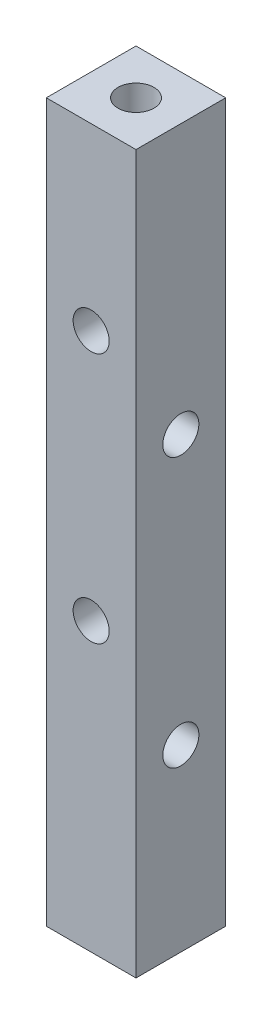
SolidWorks part; units mm, degrees
ref_plane "Front Plane" through (0, 0, 0) normal (0, 0, 1) x (1, 0, 0)
ref_plane "Top Plane" through (0, 0, 0) normal (0, 1, 0) x (1, 0, 0)
ref_plane "Right Plane" through (0, 0, 0) normal (1, 0, 0) x (0, 0, -1)
sketch "Sketch1" plane through (0, 0, 0) normal (0, 1, 0) x (1, 0, 0)
  line L1 (0, 0) -> (12.7, 0)
  line L2 (0, 0) -> (0, -12.7)
  line L3 (0, -12.7) -> (12.7, -12.7)
  line L4 (12.7, 0) -> (12.7, -12.7)
  dimension "D1" = 12.7
  dimension "D2" = 12.7
extrude "Boss-Extrude1" add sketch "Sketch1" along normal blind 101.6
sketch "Sketch4" plane through (0, 101.6, 0) normal (0, 1, 0) x (1, 0, 0)
  line L0 (12.7, 0) -> (0, 0) construction
  line L1 (0, 0) -> (0, -12.7) construction
  point P0 (6.35, -6.35)
  point P5 (6.35, -6.35)
  dimension "D1" = 6.35
  dimension "D2" = 6.35
sketch "Sketch5" plane through (0, 0, 0) normal (0, -1, 0) x (1, 0, 0)
  line L0 (12.7, 12.7) -> (12.7, 0) construction
  line L1 (0, 12.7) -> (12.7, 12.7) construction
  point P0 (6.35, 6.35)
  dimension "D1" = 6.35
  dimension "D2" = 6.35
hole_wizard "1/4-20 Tapped Hole1" positions "3DSketch1" profile "Sketch7" tap size "1/4-20" standard "ANSI Inch"
sketch3d "3DSketch1"
  point P0 (6.35, 0, 6.35)
  point P3 (6.35, 101.6, 6.35)
sketch "Sketch7" plane through (6.35, 0, 6.35) normal (1, 0, 0) x (0, 0, -1)
  line L0 (0, 0) -> (0, 18.0438)
  line L1 (0, 18.0438) -> (2.5527, 16.51)
  line L2 (2.5527, 16.51) -> (2.5527, 0)
  line L5 (2.5527, 0) -> (0, 0)
  line L10 (0, 18.0438) -> (-2.5527, 16.51) construction
  line L11 (0, -6.35) -> (0, 107.95) construction
  dimension "Tap Drill Dia." = 5.1054
  dimension "Tap Drill Depth" = 16.51
  dimension "Drill Angle" = 118
cosmetic thread "Hole Thread1" parameters "D1"=12.7, "D2"=6.35
cosmetic thread "Hole Thread2" parameters "D1"=12.7, "D2"=6.35
sketch "Sketch8" plane through (0, 0, 0) normal (0, 0, -1) x (-1, 0, 0)
  line L0 (0, 101.6) -> (0, 0) construction
  line L1 (-12.7, 101.6) -> (0, 101.6) construction
  point P0 (-6.35, 76.2)
  point P1 (-6.35, 40.64)
  dimension "D1" = 6.35
  dimension "D2" = 6.35
  dimension "D3" = 25.4
  dimension "D4" = 60.96
hole_wizard "1/4-20 Tapped Hole2" positions "3DSketch2" profile "Sketch9" tap size "1/4-20" standard "ANSI Inch"
sketch3d "3DSketch2"
  point P0 (6.35, 76.2, 0)
  point P3 (6.35, 40.64, 0)
sketch "Sketch9" plane through (6.35, 76.2, 0) normal (1, 0, 0) x (0, 1, 0)
  line L0 (0, 0) -> (0, 18.0438)
  line L1 (0, 18.0438) -> (2.5527, 16.51)
  line L2 (2.5527, 16.51) -> (2.5527, 0)
  line L5 (2.5527, 0) -> (0, 0)
  line L10 (0, 18.0438) -> (-2.5527, 16.51) construction
  line L11 (0, -6.35) -> (0, 107.95) construction
  dimension "Tap Drill Dia." = 5.1054
  dimension "Tap Drill Depth" = 16.51
  dimension "Drill Angle" = 118
cosmetic thread "Hole Thread3" parameters "D1"=12.7, "D2"=6.35
cosmetic thread "Hole Thread4" parameters "D1"=12.7, "D2"=6.35
sketch "Sketch10" plane through (12.7, 0, 0) normal (1, 0, 0) x (0, 0, -1)
  line L0 (0, 101.6) -> (0, 0) construction
  line L1 (-12.7, 0) -> (0, 0) construction
  line L2 (-12.7, 101.6) -> (-12.7, 0) construction
  point P0 (-6.35, 63.5)
  point P1 (-6.35, 25.4)
  point P4 (-6.35, 0)
  dimension "D1" = 6.35
  dimension "D2" = 25.4
  dimension "D3" = 6.35
  dimension "D4" = 63.5
hole_wizard "1/4-20 Tapped Hole3" positions "3DSketch3" profile "Sketch11" tap size "1/4-20" standard "ANSI Inch"
sketch3d "3DSketch3"
  point P0 (12.7, 25.4, 6.35)
  point P3 (12.7, 63.5, 6.35)
sketch "Sketch11" plane through (12.7, 25.4, 6.35) normal (0, 1, 0) x (0, 0, -1)
  line L0 (0, 0) -> (0, 18.0438)
  line L1 (0, 18.0438) -> (2.5527, 16.51)
  line L2 (2.5527, 16.51) -> (2.5527, 0)
  line L5 (2.5527, 0) -> (0, 0)
  line L10 (0, 18.0438) -> (-2.5527, 16.51) construction
  line L11 (0, -6.35) -> (0, 107.95) construction
  dimension "Tap Drill Dia." = 5.1054
  dimension "Tap Drill Depth" = 16.51
  dimension "Drill Angle" = 118
cosmetic thread "Hole Thread5" parameters "D1"=12.7, "D2"=6.35
cosmetic thread "Hole Thread6" parameters "D1"=12.7, "D2"=6.35
